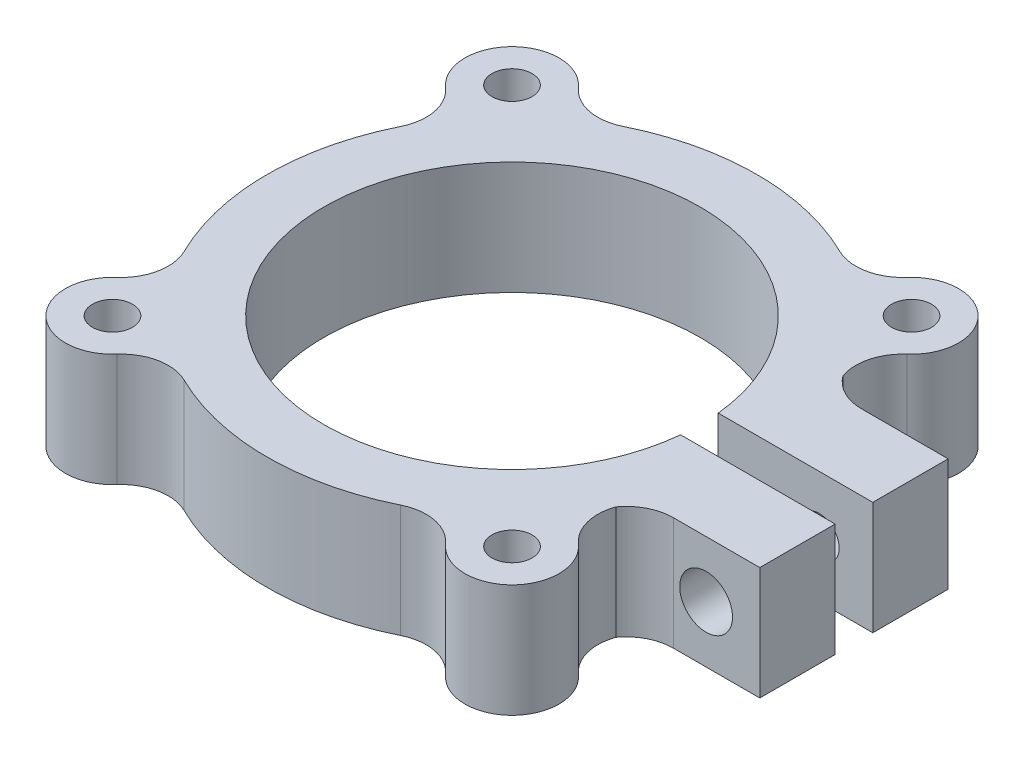
SolidWorks part; units mm, degrees
ref_plane "Front Plane" through (0, 0, 0) normal (0, 0, 1) x (1, 0, 0)
ref_plane "Top Plane" through (0, 0, 0) normal (0, 1, 0) x (1, 0, 0)
ref_plane "Right Plane" through (0, 0, 0) normal (1, 0, 0) x (0, 0, -1)
ref_plane "Plane1" through (0, 0, 0) normal (0, -1, 0) x (1, 0, 0)
sketch "Sketch1" plane through (0, 0, 0) normal (0, -1, 0) x (1, 0, 0)
  line L0 (17.2271, -6.35) -> (23.058, -6.35)
  line L1 (23.058, -6.35) -> (23.058, 6.35)
  line L2 (23.058, 6.35) -> (17.2271, 6.35)
  arc A0 (17.2271, 6.35) -> (14.6595, 7.6574) centre (17.2271, 9.525) cw
  arc A1 (14.6595, 7.6574) -> (15.5648, 11.0841) centre (17.6592, 8.6979) cw
  arc A2 (15.5648, 11.0841) -> (11.0841, 15.5648) centre (13.4704, 13.4704) ccw
  arc A3 (11.0841, 15.5648) -> (7.295, 14.8109) centre (8.6979, 17.6592) cw
  arc A4 (7.295, 14.8109) -> (-7.295, 14.8109) centre (0, 0) ccw
  arc A5 (-7.295, 14.8109) -> (-11.0841, 15.5648) centre (-8.6979, 17.6592) cw
  arc A6 (-11.0841, 15.5648) -> (-15.5648, 11.0841) centre (-13.4704, 13.4704) ccw
  arc A7 (-15.5648, 11.0841) -> (-14.8109, 7.295) centre (-17.6592, 8.6979) cw
  arc A8 (-14.8109, 7.295) -> (-14.8109, -7.295) centre (0, 0) ccw
  arc A9 (-14.8109, -7.295) -> (-15.5648, -11.0841) centre (-17.6592, -8.6979) cw
  arc A10 (-15.5648, -11.0841) -> (-11.0841, -15.5648) centre (-13.4704, -13.4704) ccw
  arc A11 (-11.0841, -15.5648) -> (-7.295, -14.8109) centre (-8.6979, -17.6592) cw
  arc A12 (-7.295, -14.8109) -> (7.295, -14.8109) centre (0, 0) ccw
  arc A13 (7.295, -14.8109) -> (11.0841, -15.5648) centre (8.6979, -17.6592) cw
  arc A14 (11.0841, -15.5648) -> (15.5648, -11.0841) centre (13.4704, -13.4704) ccw
  arc A15 (15.5648, -11.0841) -> (14.6595, -7.6574) centre (17.6592, -8.6979) cw
  arc A16 (14.6595, -7.6574) -> (17.2271, -6.35) centre (17.2271, -9.525) cw
extrude "Boss-Extrude1" add sketch "Sketch1" against normal blind 7.62
sketch "Sketch2" plane through (0, 7.62, 0) normal (0, 1, 0) x (-1, 0, 0)
  line L0 (-23.058, 1.27) -> (-23.058, -1.27)
  line L1 (-23.058, -1.27) -> (-12.6363, -1.27)
  line L2 (-12.6363, 1.27) -> (-23.058, 1.27)
  arc A0 (-12.6363, -1.27) -> (-12.6363, 1.27) centre (0, 0) cw
extrude "Cut-Extrude1" cut sketch "Sketch2" against normal through all
sketch "Sketch3" plane through (0, 0, 0) normal (0, 0, 1) x (1, 0, 0)
  line L0 (12.7, 7.62) -> (0, 7.62)
  line L1 (0, 7.62) -> (0, 0)
  line L2 (0, 0) -> (12.7, 0)
  line L3 (12.7, 0) -> (12.7, 7.62)
  line L4 (0, 7.62) -> (0, 0) construction
revolve "Cut-Revolve1" cut sketch "Sketch3" angle 360 about L4
hole_wizard "M2.5 Clearance Hole1" positions "Sketch5" profile "Sketch4" hole size "M2.5" standard "ANSI Metric"
sketch "Sketch5" plane through (0, 0, 0) normal (0, -1, 0) x (-1, 0, 0)
  point P0 (-13.4704, -13.4704)
  point P1 (13.4704, -13.4704)
  point P2 (13.4704, 13.4704)
  point P3 (-13.4704, 13.4704)
sketch "Sketch4" plane through (13.4704, 0, 13.4704) normal (1, 0, 0) x (0, 0, -1)
  line L0 (0, 0) -> (0, 7.62)
  line L1 (0, 7.62) -> (1.3525, 7.62)
  line L2 (1.3525, 7.62) -> (1.3525, 0)
  line L5 (1.3525, 0) -> (0, 0)
  line L11 (0, -6.35) -> (0, 107.95) construction
  dimension "Thru Hole Dia." = 2.7051
  dimension "Thru Hole Depth" = 7.62
hole_wizard "M3 Clearance Hole1" positions "Sketch7" profile "Sketch6" hole size "M3" standard "ANSI Metric"
sketch "Sketch7" plane through (0, 0, 6.35) normal (0, 0, 1) x (1, 0, 0)
  point P0 (19.4388, 3.81)
sketch "Sketch6" plane through (19.4388, 3.81, 6.35) normal (1, 0, 0) x (0, -1, 0)
  line L0 (0, 0) -> (0, 5.08)
  line L1 (0, 5.08) -> (1.778, 5.08)
  line L2 (1.778, 5.08) -> (1.778, 0)
  line L5 (1.778, 0) -> (0, 0)
  line L11 (0, -6.35) -> (0, 107.95) construction
  dimension "Thru Hole Dia." = 3.556
  dimension "Thru Hole Depth" = 5.08
hole_wizard "M2.5 Clearance Hole2" positions "Sketch9" profile "Sketch8" hole size "M2.5" standard "ANSI Metric"
sketch "Sketch9" plane through (0, 0, -1.27) normal (0, 0, 1) x (1, 0, 0)
  point P0 (19.4388, 3.81)
sketch "Sketch8" plane through (19.4388, 3.81, -1.27) normal (1, 0, 0) x (0, -1, 0)
  line L0 (0, 0) -> (0, 15.3754)
  line L1 (0, 15.3754) -> (1.3525, 15.3754)
  line L2 (1.3525, 15.3754) -> (1.3525, 0)
  line L5 (1.3525, 0) -> (0, 0)
  line L11 (0, -6.35) -> (0, 107.95) construction
  dimension "Thru Hole Dia." = 2.7051
  dimension "Thru Hole Depth" = 15.3754
